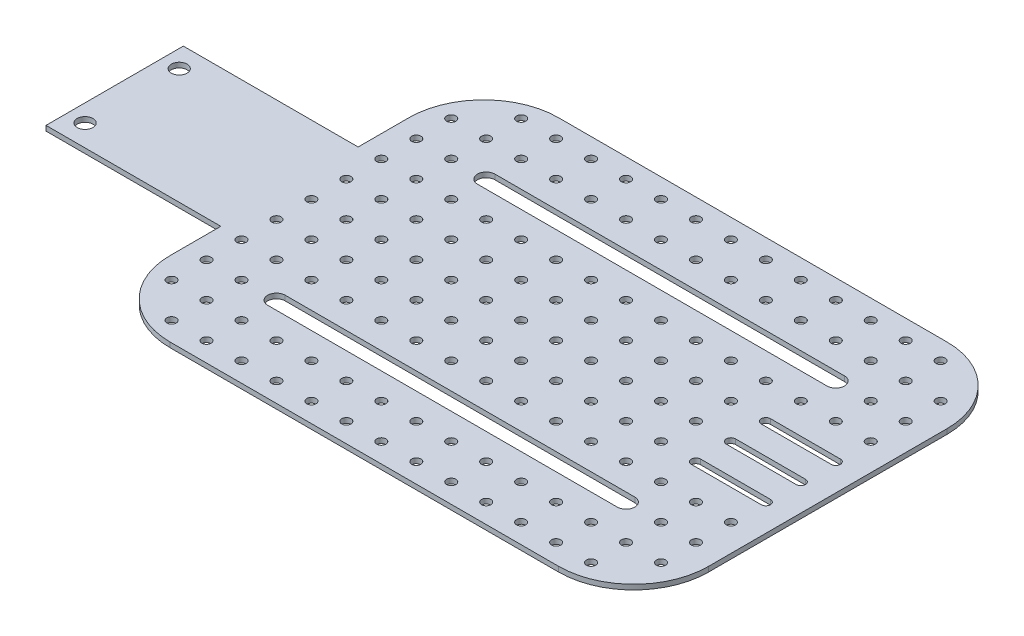
SolidWorks part; units mm, degrees
ref_plane "Front Plane" through (0, 0, 0) normal (0, 0, 1) x (1, 0, 0)
ref_plane "Top Plane" through (0, 0, 0) normal (0, 1, 0) x (1, 0, 0)
ref_plane "Right Plane" through (0, 0, 0) normal (1, 0, 0) x (0, 0, -1)
sketch "Sketch1" plane through (0, 0, 0) normal (0, 1, 0) x (1, 0, 0)
  line L0 (0, 0) -> (0, 155.575) construction
  line L1 (77.8, 155.575) -> (-77.8, 155.575)
  line L2 (-107.8, 125.575) -> (-107.8, 105.2875)
  line L3 (-107.8, 105.2875) -> (-177.8, 105.2875)
  line L4 (-177.8, 105.2875) -> (-177.8, 50.2875)
  line L5 (-177.8, 50.2875) -> (-107.8, 50.2875)
  line L6 (-107.8, 50.2875) -> (-107.8, 30)
  line L7 (-77.8, 0) -> (77.8, 0)
  line L8 (-173.4, 93.5875) -> (-173.4, 61.9875) construction
  line L9 (-177.8, 77.7875) -> (-107.8, 77.7875) construction
  line L10 (173.4, 93.5875) -> (173.4, 61.9875) construction
  line L11 (107.8, 50.2875) -> (107.8, 30)
  line L12 (177.8, 50.2875) -> (107.8, 50.2875)
  line L13 (177.8, 105.2875) -> (177.8, 50.2875)
  line L14 (107.8, 105.2875) -> (177.8, 105.2875)
  line L15 (107.8, 125.575) -> (107.8, 105.2875)
  circle A2 centre (173.4, 61.9875) radius 1.85
  circle A3 centre (173.4, 93.5875) radius 1.85
  arc A4 (107.8, 30) -> (77.8, 0) centre (77.8, 30) cw
  arc A5 (-107.8, 30) -> (-77.8, 0) centre (-77.8, 30) ccw
  arc A6 (107.8, 125.575) -> (77.8, 155.575) centre (77.8, 125.575) ccw
  arc A7 (-77.8, 155.575) -> (-107.8, 125.575) centre (-77.8, 125.575) ccw
  point P15 (-173.4, 77.7875)
  point P29 (107.8, 0)
  point P32 (-107.8, 0)
  point P35 (107.8, 155.575)
  point P38 (-107.8, 155.575)
  dimension "D8" = 30
  dimension "D1" = 155.575
  dimension "D2" = 177.8
  dimension "D3" = 55
  dimension "D4" = 31.6
  dimension "D6" = 4.4
  dimension "D7" = 70
extrude "Boss-Extrude1" add sketch "Sketch1" along normal blind 2
sketch "Sketch2" plane through (0, 2, 0) normal (0, 1, 0) x (1, 0, 0)
  line L0 (-99.0132, 8.7868) -> (-99.0132, 146.7882) construction
  line L1 (-99.0132, 146.7882) -> (99.0132, 146.7882) construction
  line L2 (99.0132, 146.7882) -> (99.0132, 8.7868) construction
  line L3 (99.0132, 8.7868) -> (-99.0132, 8.7868) construction
  line L4 (-177.8, 77.7875) -> (177.8, 77.7875) construction
  line L5 (-177.8, 105.2875) -> (-177.8, 50.2875) construction
  line L6 (177.8, 50.2875) -> (177.8, 105.2875) construction
  arc A0 (-107.8, 30) -> (-77.8, 0) centre (-77.8, 30) ccw construction
  arc A1 (-77.8, 155.575) -> (-107.8, 125.575) centre (-77.8, 125.575) ccw construction
  arc A2 (107.8, 125.575) -> (77.8, 155.575) centre (77.8, 125.575) ccw construction
  arc A3 (77.8, 0) -> (107.8, 30) centre (77.8, 30) ccw construction
  circle A4 centre (-99.0132, 21.7875) radius 1.85
  circle A5 centre (-99.0132, 35.7875) radius 1.85
  circle A6 centre (-99.0132, 49.7875) radius 1.85
  circle A7 centre (-99.0132, 63.7875) radius 1.85
  circle A8 centre (-99.0132, 77.7875) radius 1.85
  circle A9 centre (-99.0132, 91.7875) radius 1.85
  circle A10 centre (-99.0132, 105.7875) radius 1.85
  circle A11 centre (-99.0132, 119.7875) radius 1.85
  circle A12 centre (-99.0132, 133.7875) radius 1.85
  circle A13 centre (-85.0132, 63.7875) radius 1.85
  circle A14 centre (-85.0132, 49.7875) radius 1.85
  circle A15 centre (-85.0132, 35.7875) radius 1.85
  circle A16 centre (-85.0132, 21.7875) radius 1.85
  circle A17 centre (-85.0132, 91.7875) radius 1.85
  circle A18 centre (-85.0132, 105.7875) radius 1.85
  circle A19 centre (-85.0132, 77.7875) radius 1.85
  circle A20 centre (-85.0132, 133.7875) radius 1.85
  circle A21 centre (-85.0132, 119.7875) radius 1.85
  circle A22 centre (-71.0132, 63.7875) radius 1.85
  circle A23 centre (-71.0132, 49.7875) radius 1.85
  circle A24 centre (-71.0132, 35.7875) radius 1.85
  circle A25 centre (-71.0132, 21.7875) radius 1.85
  circle A26 centre (-71.0132, 91.7875) radius 1.85
  circle A27 centre (-71.0132, 105.7875) radius 1.85
  circle A28 centre (-71.0132, 77.7875) radius 1.85
  circle A29 centre (-71.0132, 133.7875) radius 1.85
  circle A30 centre (-71.0132, 119.7875) radius 1.85
  circle A31 centre (-57.0132, 63.7875) radius 1.85
  circle A32 centre (-57.0132, 49.7875) radius 1.85
  circle A33 centre (-57.0132, 35.7875) radius 1.85
  circle A34 centre (-57.0132, 21.7875) radius 1.85
  circle A35 centre (-57.0132, 91.7875) radius 1.85
  circle A36 centre (-57.0132, 105.7875) radius 1.85
  circle A37 centre (-57.0132, 77.7875) radius 1.85
  circle A38 centre (-57.0132, 133.7875) radius 1.85
  circle A39 centre (-57.0132, 119.7875) radius 1.85
  circle A40 centre (-43.0132, 63.7875) radius 1.85
  circle A41 centre (-43.0132, 49.7875) radius 1.85
  circle A42 centre (-43.0132, 35.7875) radius 1.85
  circle A43 centre (-43.0132, 21.7875) radius 1.85
  circle A44 centre (-43.0132, 91.7875) radius 1.85
  circle A45 centre (-43.0132, 105.7875) radius 1.85
  circle A46 centre (-43.0132, 77.7875) radius 1.85
  circle A47 centre (-43.0132, 133.7875) radius 1.85
  circle A48 centre (-43.0132, 119.7875) radius 1.85
  circle A49 centre (-29.0132, 63.7875) radius 1.85
  circle A50 centre (-29.0132, 49.7875) radius 1.85
  circle A51 centre (-29.0132, 35.7875) radius 1.85
  circle A52 centre (-29.0132, 21.7875) radius 1.85
  circle A53 centre (-29.0132, 91.7875) radius 1.85
  circle A54 centre (-29.0132, 105.7875) radius 1.85
  circle A55 centre (-29.0132, 77.7875) radius 1.85
  circle A56 centre (-29.0132, 133.7875) radius 1.85
  circle A57 centre (-29.0132, 119.7875) radius 1.85
  circle A58 centre (-15.0132, 63.7875) radius 1.85
  circle A59 centre (-15.0132, 49.7875) radius 1.85
  circle A60 centre (-15.0132, 35.7875) radius 1.85
  circle A61 centre (-15.0132, 21.7875) radius 1.85
  circle A62 centre (-15.0132, 91.7875) radius 1.85
  circle A63 centre (-15.0132, 105.7875) radius 1.85
  circle A64 centre (-15.0132, 77.7875) radius 1.85
  circle A65 centre (-15.0132, 133.7875) radius 1.85
  circle A66 centre (-15.0132, 119.7875) radius 1.85
  circle A67 centre (-1.0132, 63.7875) radius 1.85
  circle A68 centre (-1.0132, 49.7875) radius 1.85
  circle A69 centre (-1.0132, 35.7875) radius 1.85
  circle A70 centre (-1.0132, 21.7875) radius 1.85
  circle A71 centre (-1.0132, 91.7875) radius 1.85
  circle A72 centre (-1.0132, 105.7875) radius 1.85
  circle A73 centre (-1.0132, 77.7875) radius 1.85
  circle A74 centre (-1.0132, 133.7875) radius 1.85
  circle A75 centre (-1.0132, 119.7875) radius 1.85
  circle A76 centre (12.9868, 63.7875) radius 1.85
  circle A77 centre (12.9868, 49.7875) radius 1.85
  circle A78 centre (12.9868, 35.7875) radius 1.85
  circle A79 centre (12.9868, 21.7875) radius 1.85
  circle A80 centre (12.9868, 91.7875) radius 1.85
  circle A81 centre (12.9868, 105.7875) radius 1.85
  circle A82 centre (12.9868, 77.7875) radius 1.85
  circle A83 centre (12.9868, 133.7875) radius 1.85
  circle A84 centre (12.9868, 119.7875) radius 1.85
  circle A85 centre (26.9868, 63.7875) radius 1.85
  circle A86 centre (26.9868, 49.7875) radius 1.85
  circle A87 centre (26.9868, 35.7875) radius 1.85
  circle A88 centre (26.9868, 21.7875) radius 1.85
  circle A89 centre (26.9868, 91.7875) radius 1.85
  circle A90 centre (26.9868, 105.7875) radius 1.85
  circle A91 centre (26.9868, 77.7875) radius 1.85
  circle A92 centre (26.9868, 133.7875) radius 1.85
  circle A93 centre (26.9868, 119.7875) radius 1.85
  circle A94 centre (40.9868, 63.7875) radius 1.85
  circle A95 centre (40.9868, 49.7875) radius 1.85
  circle A96 centre (40.9868, 35.7875) radius 1.85
  circle A97 centre (40.9868, 21.7875) radius 1.85
  circle A98 centre (40.9868, 91.7875) radius 1.85
  circle A99 centre (40.9868, 105.7875) radius 1.85
  circle A100 centre (40.9868, 77.7875) radius 1.85
  circle A101 centre (40.9868, 133.7875) radius 1.85
  circle A102 centre (40.9868, 119.7875) radius 1.85
  circle A103 centre (54.9868, 63.7875) radius 1.85
  circle A104 centre (54.9868, 49.7875) radius 1.85
  circle A105 centre (54.9868, 35.7875) radius 1.85
  circle A106 centre (54.9868, 21.7875) radius 1.85
  circle A107 centre (54.9868, 91.7875) radius 1.85
  circle A108 centre (54.9868, 105.7875) radius 1.85
  circle A109 centre (54.9868, 77.7875) radius 1.85
  circle A110 centre (54.9868, 133.7875) radius 1.85
  circle A111 centre (54.9868, 119.7875) radius 1.85
  circle A112 centre (68.9868, 63.7875) radius 1.85
  circle A113 centre (68.9868, 49.7875) radius 1.85
  circle A114 centre (68.9868, 35.7875) radius 1.85
  circle A115 centre (68.9868, 21.7875) radius 1.85
  circle A116 centre (68.9868, 91.7875) radius 1.85
  circle A117 centre (68.9868, 105.7875) radius 1.85
  circle A118 centre (68.9868, 77.7875) radius 1.85
  circle A119 centre (68.9868, 133.7875) radius 1.85
  circle A120 centre (68.9868, 119.7875) radius 1.85
  circle A121 centre (82.9868, 63.7875) radius 1.85
  circle A122 centre (82.9868, 49.7875) radius 1.85
  circle A123 centre (82.9868, 35.7875) radius 1.85
  circle A124 centre (82.9868, 21.7875) radius 1.85
  circle A125 centre (82.9868, 91.7875) radius 1.85
  circle A126 centre (82.9868, 105.7875) radius 1.85
  circle A127 centre (82.9868, 77.7875) radius 1.85
  circle A128 centre (82.9868, 133.7875) radius 1.85
  circle A129 centre (82.9868, 119.7875) radius 1.85
  circle A130 centre (96.9868, 63.7875) radius 1.85
  circle A131 centre (96.9868, 49.7875) radius 1.85
  circle A132 centre (96.9868, 35.7875) radius 1.85
  circle A133 centre (96.9868, 21.7875) radius 1.85
  circle A134 centre (96.9868, 91.7875) radius 1.85
  circle A135 centre (96.9868, 105.7875) radius 1.85
  circle A136 centre (96.9868, 77.7875) radius 1.85
  circle A137 centre (96.9868, 133.7875) radius 1.85
  circle A138 centre (96.9868, 119.7875) radius 1.85
  circle A139 centre (-85.0132, 147.7875) radius 1.85
  circle A140 centre (-1.0132, 147.7875) radius 1.85
  circle A141 centre (-15.0132, 147.7875) radius 1.85
  circle A142 centre (-29.0132, 147.7875) radius 1.85
  circle A143 centre (-43.0132, 147.7875) radius 1.85
  circle A144 centre (-57.0132, 147.7875) radius 1.85
  circle A145 centre (-71.0132, 147.7875) radius 1.85
  circle A146 centre (12.9868, 147.7875) radius 1.85
  circle A147 centre (26.9868, 147.7875) radius 1.85
  circle A148 centre (82.9868, 147.7875) radius 1.85
  circle A149 centre (68.9868, 147.7875) radius 1.85
  circle A150 centre (54.9868, 147.7875) radius 1.85
  circle A151 centre (40.9868, 147.7875) radius 1.85
  circle A152 centre (-85.0132, 35.7875) radius 1.85
  circle A153 centre (-85.0132, 7.7875) radius 1.85
  circle A154 centre (-71.0132, 7.7875) radius 1.85
  circle A155 centre (-57.0132, 7.7875) radius 1.85
  circle A156 centre (-43.0132, 7.7875) radius 1.85
  circle A157 centre (-29.0132, 7.7875) radius 1.85
  circle A158 centre (-15.0132, 7.7875) radius 1.85
  circle A159 centre (-1.0132, 7.7875) radius 1.85
  circle A160 centre (12.9868, 7.7875) radius 1.85
  circle A161 centre (26.9868, 7.7875) radius 1.85
  circle A162 centre (40.9868, 7.7875) radius 1.85
  circle A163 centre (54.9868, 7.7875) radius 1.85
  circle A164 centre (68.9868, 7.7875) radius 1.85
  circle A165 centre (82.9868, 7.7875) radius 1.85
  dimension "D1" = 3.7
  dimension "D2" = 9
  dimension "D3" = 15
  dimension "D4" = 2
  dimension "D5" = 2
extrude "Cut-Extrude1" cut sketch "Sketch2" against normal blind 2
sketch "Sketch3" plane through (177.8, 0, 0) normal (1, 0, 0) x (0, 0, -1)
  line L4 (50.2875, 0) -> (105.2875, 0)
  line L5 (105.2875, 0) -> (105.2875, 2)
  line L6 (105.2875, 2) -> (50.2875, 2)
  line L7 (50.2875, 2) -> (50.2875, 0)
  line L8 (50.2875, 0) -> (105.2875, 0)
  line L9 (105.2875, 0) -> (105.2875, 2)
  line L10 (105.2875, 2) -> (50.2875, 2)
  line L11 (50.2875, 2) -> (50.2875, 0)
  dimension "D1" = 0
extrude "Cut-Extrude2" cut sketch "Sketch3" against normal up to surface (70 mm away) up to face at (107.8, 1, -115.4312)
sketch "Sketch4" plane through (0, 2, 0) normal (0, 1, 0) x (1, 0, 0)
  line L0 (-177.8, 77.7875) -> (107.8, 77.7875) construction
  line L1 (-177.8, 105.2875) -> (-177.8, 50.2875) construction
  line L2 (107.8, 30) -> (107.8, 125.575) construction
  circle A0 centre (-170.8, 96.6375) radius 3.15
  circle A1 centre (-170.8, 58.9375) radius 3.15
  dimension "D2" = 6.3
  dimension "D1" = 18.85
  dimension "D3" = 7
extrude "Cut-Extrude3" cut sketch "Sketch4" against normal blind 10 contours A0 | A1
sketch "Sketch5" plane through (0, 2, 0) normal (0, 1, 0) x (1, 0, 0)
  line L0 (-71.0132, 119.7875) -> (68.9868, 119.7875) construction
  line L1 (-71.0132, 123.2875) -> (68.9868, 123.2875)
  line L2 (-71.0132, 116.2875) -> (68.9868, 116.2875)
  line L3 (-71.0132, 35.7875) -> (68.9868, 35.7875) construction
  line L4 (-71.0132, 39.2875) -> (68.9868, 39.2875)
  line L5 (-71.0132, 32.2875) -> (68.9868, 32.2875)
  arc A0 (-71.0132, 123.2875) -> (-71.0132, 116.2875) centre (-71.0132, 119.7875) ccw
  arc A1 (68.9868, 116.2875) -> (68.9868, 123.2875) centre (68.9868, 119.7875) ccw
  arc A2 (-71.0132, 39.2875) -> (-71.0132, 32.2875) centre (-71.0132, 35.7875) ccw
  arc A3 (68.9868, 32.2875) -> (68.9868, 39.2875) centre (68.9868, 35.7875) ccw
  point P4 (-1.0132, 119.7875)
  point P9 (-1.0132, 35.7875)
  dimension "D1" = 3.5
  dimension "D2" = 3.5
extrude "Cut-Extrude4" cut sketch "Sketch5" against normal blind 10 contours L2 A1 L1 A0 | L5 A3 L4 A2
sketch "Sketch6" plane through (0, 2, 0) normal (0, 1, 0) x (1, 0, 0)
  line L0 (68.9868, 91.7875) -> (96.9868, 91.7875) construction
  line L1 (68.9868, 93.6375) -> (96.9868, 93.6375)
  line L2 (68.9868, 89.9375) -> (96.9868, 89.9375)
  line L3 (68.9868, 77.7875) -> (96.9868, 77.7875) construction
  line L4 (68.9868, 79.6375) -> (96.9868, 79.6375)
  line L5 (68.9868, 75.9375) -> (96.9868, 75.9375)
  line L6 (96.9868, 63.7875) -> (68.9868, 63.7875) construction
  line L7 (96.9868, 61.9375) -> (68.9868, 61.9375)
  line L8 (96.9868, 65.6375) -> (68.9868, 65.6375)
  circle A0 centre (96.9868, 63.7875) radius 1.85 construction
  circle A1 centre (82.9868, 63.7875) radius 1.85 construction
  circle A2 centre (68.9868, 63.7875) radius 1.85 construction
  circle A3 centre (96.9868, 77.7875) radius 1.85 construction
  circle A4 centre (82.9868, 77.7875) radius 1.85 construction
  circle A5 centre (68.9868, 77.7875) radius 1.85 construction
  circle A6 centre (68.9868, 91.7875) radius 1.85 construction
  circle A7 centre (82.9868, 91.7875) radius 1.85 construction
  circle A8 centre (96.9868, 91.7875) radius 1.85 construction
  circle A9 centre (96.9868, 63.7875) radius 1.85
  circle A10 centre (82.9868, 63.7875) radius 1.85
  circle A11 centre (68.9868, 63.7875) radius 1.85
  circle A12 centre (96.9868, 77.7875) radius 1.85
  circle A13 centre (82.9868, 77.7875) radius 1.85
  circle A14 centre (68.9868, 77.7875) radius 1.85
  circle A15 centre (68.9868, 91.7875) radius 1.85
  circle A16 centre (82.9868, 91.7875) radius 1.85
  circle A17 centre (96.9868, 91.7875) radius 1.85
  arc A18 (68.9868, 93.6375) -> (68.9868, 89.9375) centre (68.9868, 91.7875) ccw
  arc A19 (96.9868, 89.9375) -> (96.9868, 93.6375) centre (96.9868, 91.7875) ccw
  arc A20 (68.9868, 79.6375) -> (68.9868, 75.9375) centre (68.9868, 77.7875) ccw
  arc A21 (96.9868, 75.9375) -> (96.9868, 79.6375) centre (96.9868, 77.7875) ccw
  arc A22 (96.9868, 61.9375) -> (96.9868, 65.6375) centre (96.9868, 63.7875) ccw
  arc A23 (68.9868, 65.6375) -> (68.9868, 61.9375) centre (68.9868, 63.7875) ccw
  point P27 (82.9868, 91.7875)
  point P32 (82.9868, 77.7875)
  point P37 (82.9868, 63.7875)
  point P42 (68.9868, 75.3492)
extrude "Cut-Extrude5" cut sketch "Sketch6" against normal through all contours A13 L5 A12 L4 | A17 L1 A16 L2 | A16 L1 A15 L2 | A16 | A15 | A14 | A13 | A12 | A17 | A14 L5 A13 L4 | A11 | A11 L7 A10 L8 | A10 | A10 L7 A9 L8 | A9 L5
